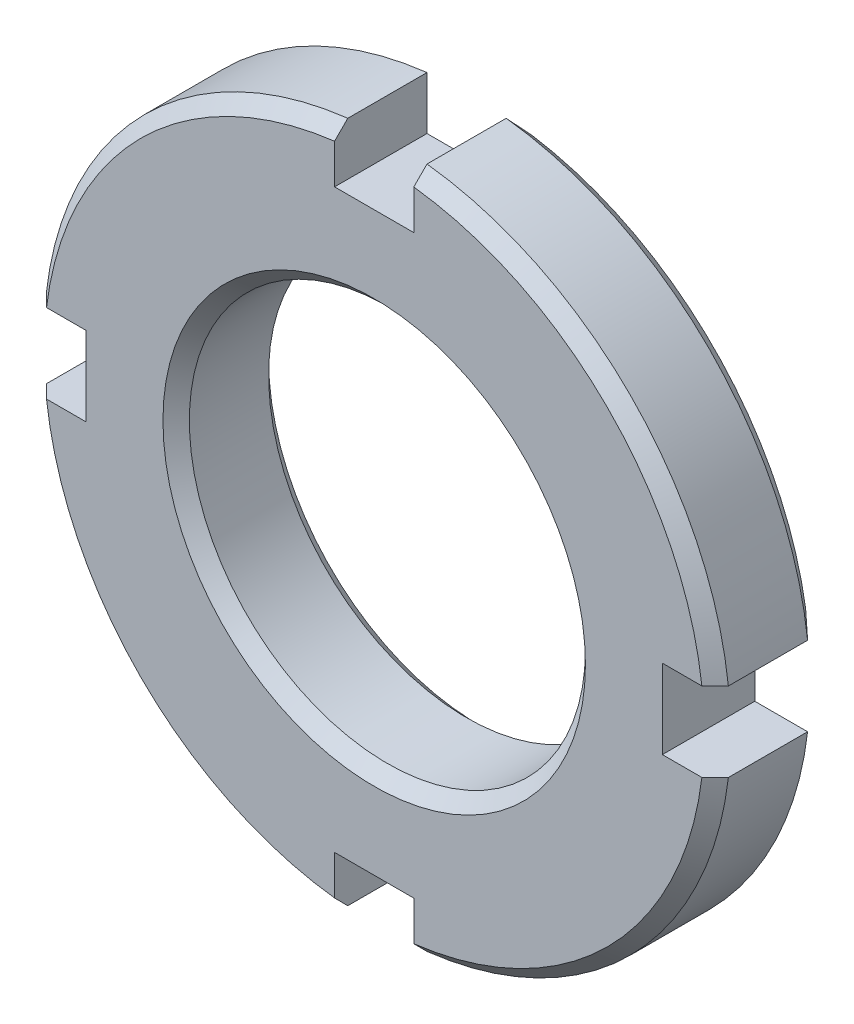
SolidWorks part; units mm, degrees
material "Сталь 45 ГОСТ 535-88"
ref_plane "Спереди" through (0, 0, 0) normal (0, 0, 1) x (1, 0, 0)
ref_plane "Сверху" through (0, 0, 0) normal (0, 1, 0) x (1, 0, 0)
ref_plane "Справа" through (0, 0, 0) normal (1, 0, 0) x (0, 0, -1)
sketch "Эскиз1" plane through (0, 0, 0) normal (0, 0, 1) x (1, 0, 0)
  line L0 (0, 12.9132) -> (0, -12.9132) construction
  line L1 (12.9132, 0) -> (-12.9132, 0) construction
  line L3 (1.5, 12.9132) -> (-1.6237, 12.9132) construction
  line L4 (1.5, 12.9132) -> (1.5, 10.9132)
  line L5 (1.5, 10.9132) -> (-1.5, 10.9132)
  line L6 (-1.5, 12.9132) -> (-1.5, 10.9132)
  line L7 (12.9132, 1.5) -> (10.9132, 1.5)
  line L8 (12.9132, 1.5) -> (12.9132, -1.5) construction
  line L9 (12.9132, -1.5) -> (10.9132, -1.5)
  line L10 (10.9132, 1.5) -> (10.9132, -1.5)
  line L11 (-12.9132, 1.5) -> (-10.9132, 1.5)
  line L12 (-12.9132, 1.5) -> (-12.9132, -1.5) construction
  line L13 (-12.9132, -1.5) -> (-10.9132, -1.5)
  line L14 (-10.9132, 1.5) -> (-10.9132, -1.5)
  line L15 (1.5, -10.9132) -> (-1.5, -10.9132)
  line L16 (1.5, -10.9132) -> (1.5, -12.9132)
  line L17 (1.5, -12.9132) -> (-1.5, -12.9132) construction
  line L18 (-1.5, -10.9132) -> (-1.5, -12.9132)
  arc A0 (-1.5, 12.9132) -> (-12.9132, 1.5) centre (0, 0) ccw
  circle A1 centre (0, 0) radius 7.5
  arc A2 (1.5, -12.9132) -> (12.9132, -1.5) centre (0, 0) ccw
  arc A3 (12.9132, 1.5) -> (1.5, 12.9132) centre (0, 0) ccw
  arc A4 (-12.9132, -1.5) -> (-1.5, -12.9132) centre (0, 0) ccw
  circle A5 centre (0, 0) radius 10.9132 construction
  dimension "D1" = 15
  dimension "D2" = 26
  dimension "D4" = 2
  dimension "D3" = 3
extrude "Бобышка-Вытянуть1" add sketch "Эскиз1" along normal blind 4
cosmetic thread "Условное изображение резьбы1" parameters "D2"=16
chamfer "Фаска1" distance 0.5 angle 45 22 edges at (-11.9132, 1.5, 0) (-10.9132, 0, 0) (-11.9132, -1.5, 0) (-9.1924, -9.1924, 0) (-1.5, -11.9132, 0) (0, -10.9132, 0) (1.5, -11.9132, 0) (9.1924, -9.1924, 0) (11.9132, -1.5, 0) (10.9132, 0, 0) (11.9132, 1.5, 0) (9.1924, 9.1924, 0) (1.5, 11.9132, 0) (0, 10.9132, 0) (-1.5, 11.9132, 0) (-9.1924, 9.1924, 0) (7.5, 0, 0) (7.5, 0, 4) (-9.1924, -9.1924, 4) (9.1924, -9.1924, 4) (9.1924, 9.1924, 4) (-9.1924, 9.1924, 4)
